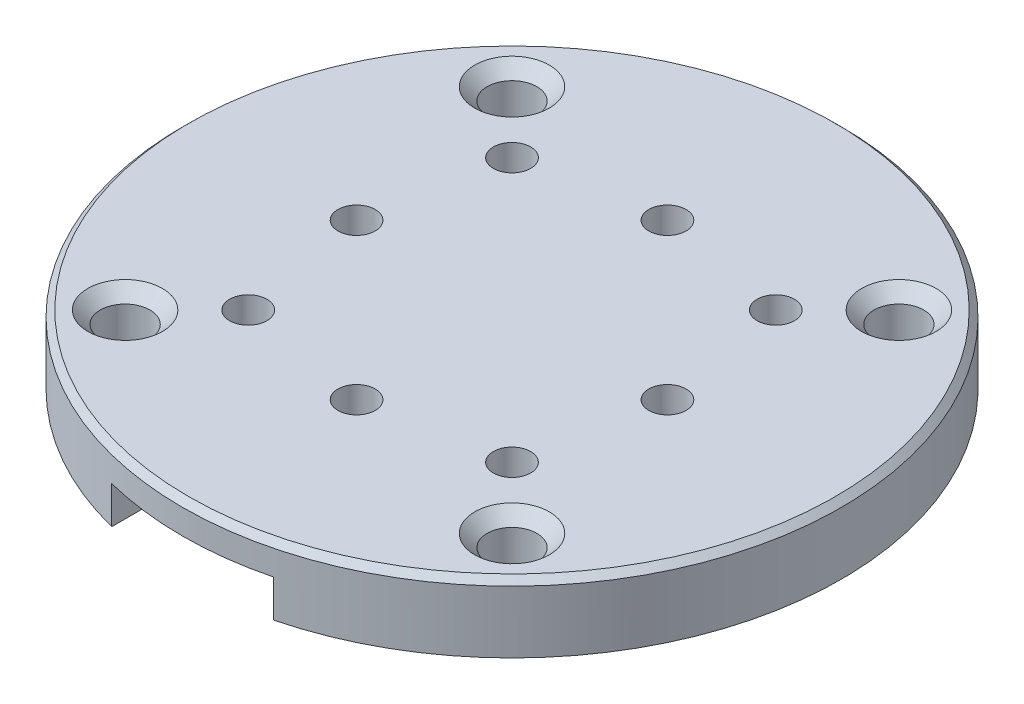
SolidWorks part; units mm, degrees
ref_plane "Спереди" through (0, 0, 0) normal (0, 0, 1) x (1, 0, 0)
ref_plane "Сверху" through (0, 0, 0) normal (0, 1, 0) x (1, 0, 0)
ref_plane "Справа" through (0, 0, 0) normal (1, 0, 0) x (0, 0, -1)
sketch "Эскиз1" plane through (0, 0, 0) normal (0, 1, 0) x (1, 0, 0)
  circle A0 centre (0, 0) radius 26.5
  dimension "D1" = 53
extrude "Бобышка-Вытянуть1" add sketch "Эскиз1" along normal blind 5.5
chamfer "Фаска1" distance 0.5 angle 45 1 edges at (0, 5.5, 26.5)
sketch "Эскиз4" plane through (0, 5.5, 0) normal (0, 1, 0) x (1, 0, 0)
  circle A0 centre (-15.5563, 15.5563) radius 2
  circle A1 centre (-15.5563, -15.5563) radius 2
  circle A2 centre (15.5563, -15.5563) radius 2
  circle A3 centre (15.5563, 15.5563) radius 2
  point P9 (0, 0)
  line B0 (0, 0) -> (12.5, 0) construction
  line B1 (10.6066, 10.6066) -> (15.5563, 15.5563) construction
  line B2 (0, 0) -> (10.6066, 10.6066) construction
  circle B3 centre (15.5563, 15.5563) radius 1.5 construction
  circle B4 centre (15.5563, -15.5563) radius 1.5 construction
  circle B5 centre (-15.5563, -15.5563) radius 1.5 construction
  circle B6 centre (-15.5563, 15.5563) radius 1.5 construction
  dimension "D1" = 4
sketch_block_instance "GBM6216-150T-Stator-MountingHoles-1"
sketch_block "Блок2" parameters "D1"=45, "D2"=12.5, "D3"=15, "D4"=22
extrude "Вырез-Вытянуть2" cut sketch "Эскиз4" against normal through all contours A0 | A3 | A2 | A1
chamfer "Фаска2" distance 1 angle 45 4 edges at (-15.5563, 5.5, 17.5563) (15.5563, 5.5, 17.5563) (15.5563, 5.5, -13.5563) (-15.5563, 5.5, -13.5563)
sketch "Эскиз5" plane through (0, 5.5, 0) normal (0, 1, 0) x (1, 0, 0)
  circle B0 centre (0, 12.5) radius 1.5
  circle B1 centre (12.5, 0) radius 1.5
  circle B2 centre (0, -12.5) radius 1.5
  circle B3 centre (-12.5, 0) radius 1.5
  circle B4 centre (10.6066, 10.6066) radius 1.5
  circle B5 centre (10.6066, -10.6066) radius 1.5
  circle B6 centre (-10.6066, -10.6066) radius 1.5
  circle B7 centre (-10.6066, 10.6066) radius 1.5
sketch_block_instance "GBM6216-150T-Rotor-MountingHoles-1"
sketch_block "GBM6216-150T-Rotor-MountingHoles" parameters "D4"=3, "D5"=3, "D1"=12.5, "D2"=15, "D3"=45
extrude "Вырез-Вытянуть3" cut sketch "Эскиз5" against normal through all
sketch "Эскиз6" plane through (0, 0, 0) normal (0, -1, 0) x (1, 0, 0)
  line L0 (0, 0) -> (0, 26.5) construction
  line L1 (6.5, 6.9282) -> (6.5, 25.6905)
  line L2 (-6.5, 6.9282) -> (-6.5, 25.6905)
  arc A0 (-6.5, 6.9282) -> (6.5, 6.9282) centre (0, 0) ccw
  circle A2 centre (0, 0) radius 26.5 construction
  arc A3 (6.5, 25.6905) -> (-6.5, 25.6905) centre (0, 0) ccw
  dimension "D1" = 19
  dimension "D2" = 6.5
extrude "Вырез-Вытянуть4" cut sketch "Эскиз6" against normal blind 3
